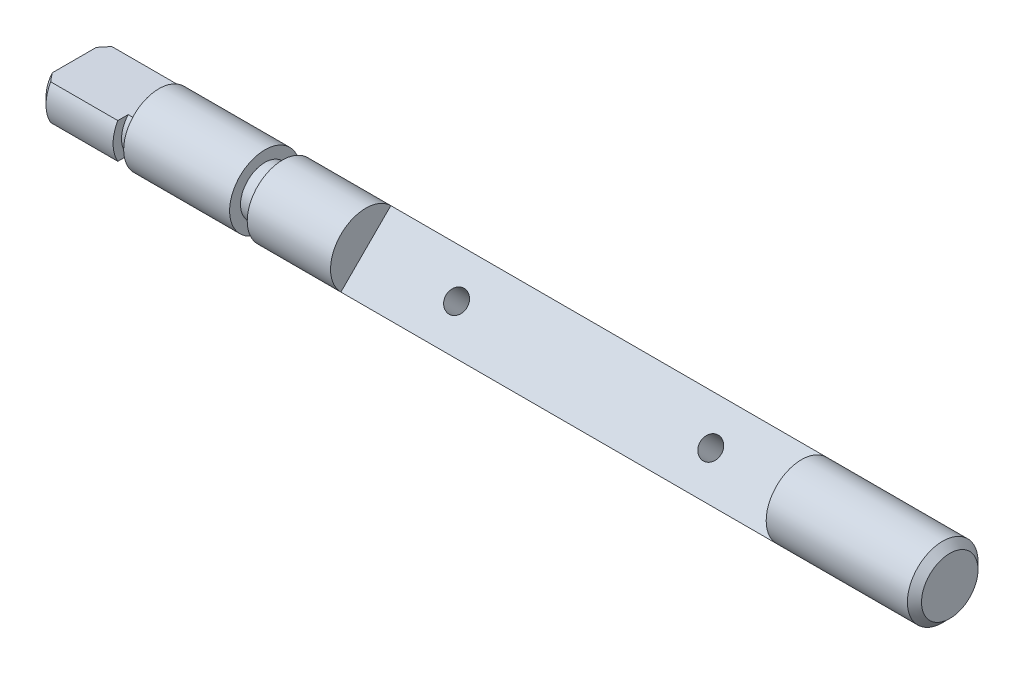
SolidWorks part; units mm, degrees
ref_plane "Alzado" through (0, 0, 0) normal (0, 0, 1) x (1, 0, 0)
ref_plane "Planta" through (0, 0, 0) normal (0, 1, 0) x (1, 0, 0)
ref_plane "Vista lateral" through (0, 0, 0) normal (1, 0, 0) x (0, 0, -1)
sketch "Sketch1" plane through (0, 0, 0) normal (1, 0, 0) x (0, 0, -1)
  circle A0 centre (0, 0) radius 5
  dimension "D1" = 10
extrude "Boss-Extrude1" add sketch "Sketch1" along normal blind 21
chamfer "Chamfer1" distance 1 angle 45 1 edges at (21, 0, -5)
sketch "Sketch2" plane through (0, 0, 0) normal (-1, 0, 0) x (0, 0, 1)
  line L0 (-3.5355, 3.5355) -> (3.5355, -3.5355)
  line L1 (-5.7685, 0) -> (8.316, 0) construction
  arc A0 (-3.5355, 3.5355) -> (3.5355, -3.5355) centre (0, 0) ccw
  circle A1 centre (0, 0) radius 5 construction
  point P12 (0, 0)
  dimension "D1" = 45
extrude "Boss-Extrude2" add sketch "Sketch2" along normal blind 61.7
sketch "Sketch3" plane through (-61.7, 0, 0) normal (-1, 0, 0) x (0, 0, 1)
  circle A0 centre (0, 0) radius 5
  dimension "D1" = 10
extrude "Boss-Extrude5" add sketch "Sketch3" along normal blind 11.8
sketch "Sketch5" plane through (-73.5, 0, 0) normal (-1, 0, 0) x (0, 0, 1)
  circle A0 centre (0, 0) radius 3.45
  dimension "D1" = 6.9
extrude "Boss-Extrude6" add sketch "Sketch5" along normal blind 2.5
sketch "Sketch6" plane through (-76, 0, 0) normal (-1, 0, 0) x (0, 0, 1)
  circle A0 centre (0, 0) radius 5
  dimension "D1" = 10
extrude "Boss-Extrude7" add sketch "Sketch6" along normal blind 15
sketch "Sketch7" plane through (-91, 0, 0) normal (-1, 0, 0) x (0, 0, 1)
  line L1 (-2.8618, 2.5) -> (2.8618, 2.5)
  line L3 (-2.8618, -2.5) -> (2.8618, -2.5)
  arc A0 (-2.8618, 2.5) -> (-2.8618, -2.5) centre (0, 0) ccw
  arc A1 (2.8618, -2.5) -> (2.8618, 2.5) centre (0, 0) ccw
  point P2 (0, 2.5)
  point P10 (0, -2.5)
  dimension "D1" = 7.6
  dimension "D2" = 5
extrude "Boss-Extrude8" add sketch "Sketch7" along normal blind 1.5
sketch "Sketch9" plane through (-92.5, 0, 0) normal (-1, 0, 0) x (0, 0, 1)
  circle A0 centre (0, 0) radius 5
  dimension "D1" = 10
extrude "Boss-Extrude10" add sketch "Sketch9" along normal blind 10.5
cosmetic thread "Cosmetic Thread6" parameters "D2"=8.891
cosmetic thread "Cosmetic Thread7" parameters "D2"=8.891
chamfer "Chamfer3" distance 1 angle 45 1 edges at (-103, 0, 5)
sketch "Sketch10" plane through (-103, 0, 0) normal (-1, 0, 0) x (0, 0, 1)
  line L0 (-4.3301, 2.5) -> (4.3301, 2.5)
  line L1 (-4.3301, -2.5) -> (4.3301, -2.5)
  arc A0 (-4.3301, -2.5) -> (4.3301, -2.5) centre (0, 0) ccw
  arc A1 (4.3301, 2.5) -> (-4.3301, 2.5) centre (0, 0) ccw
  point P7 (0, 2.5)
  point P8 (0, -2.5)
  dimension "D1" = 10
  dimension "D2" = 5
extrude "Cut-Extrude1" cut sketch "Sketch10" against normal blind 10.5
sketch "Sketch11" plane through (0, 0, 0) normal (0, 0.7071, 0.7071) x (1, 0, 0)
  line L0 (-61.7, -5) -> (-61.7, 5) construction
  circle A0 centre (-12.85, 0) radius 1.5
  circle A1 centre (-48.85, 0) radius 1.5
  dimension "D1" = 36
  dimension "D2" = 3
  dimension "D3" = 12.85
extrude "Cut-Extrude2" cut sketch "Sketch11" against normal blind 10.5
cosmetic thread "Cosmetic Thread4" parameters "D1"=5, "D2"=4
cosmetic thread "Cosmetic Thread5" parameters "D1"=5, "D2"=4
